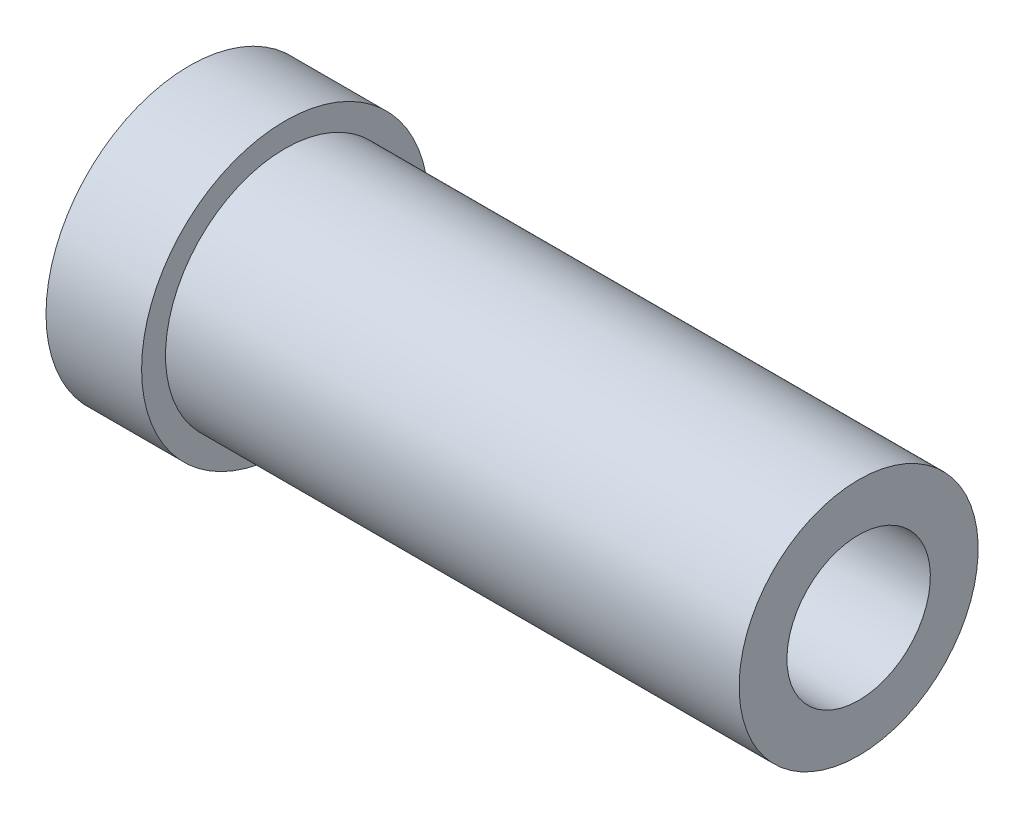
SolidWorks part; units mm, degrees
material "1023 Carbon Steel Sheet (SS)"
ref_plane "Front Plane" through (0, 0, 0) normal (0, 0, 1) x (1, 0, 0)
ref_plane "Top Plane" through (0, 0, 0) normal (0, 1, 0) x (1, 0, 0)
ref_plane "Right Plane" through (0, 0, 0) normal (1, 0, 0) x (0, 0, -1)
sketch "Sketch1" plane through (0, 0, 0) normal (0, 0, 1) x (1, 0, 0)
  line L0 (0, 0) -> (13.2091, 0) construction
  line L1 (3.6256, 2.5) -> (15.6256, 2.5)
  line L2 (15.6256, 2.5) -> (15.6256, 1.5)
  line L3 (15.6256, 1.5) -> (3.6256, 1.5)
  line L4 (3.6256, 1.5) -> (3.6256, 0)
  line L5 (3.6256, 2.5) -> (3.6256, 3)
  line L6 (3.6256, 3) -> (1.6256, 3)
  line L7 (1.6256, 3) -> (1.6256, 0)
  line L8 (3.6256, 0) -> (1.6256, 0)
  dimension "D1" = 12
  dimension "D2" = 2.5
  dimension "D3" = 1.5
  dimension "D4" = 2
  dimension "D5" = 2
  dimension "D6" = 3
revolve "Revolve1" add sketch "Sketch1" angle 360 about L0
